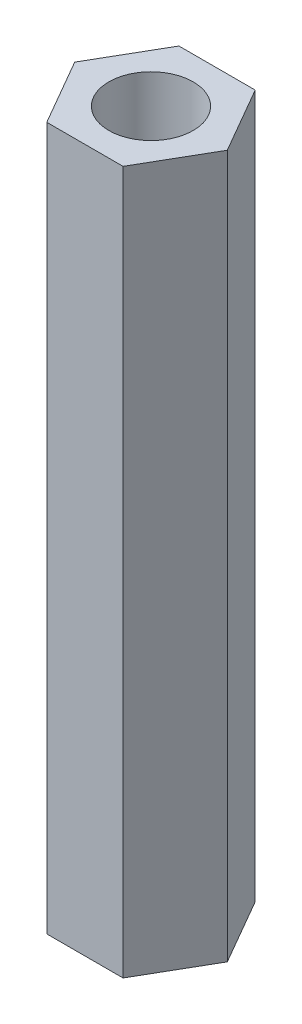
SolidWorks part; units mm, degrees
material "黄铜"
ref_plane "前视基准面" through (0, 0, 0) normal (0, 0, 1) x (1, 0, 0)
ref_plane "上视基准面" through (0, 0, 0) normal (0, 1, 0) x (1, 0, 0)
ref_plane "右视基准面" through (0, 0, 0) normal (1, 0, 0) x (0, 0, -1)
other "Configuration Table"
sketch "草图1" plane through (0, 0, 0) normal (0, 1, 0) x (1, 0, 0)
  line L0 (-2.7135, 0) -> (2.7135, 0) construction
  line L1 (1.3568, -2.35) -> (2.7135, 0)
  line L2 (2.7135, 0) -> (1.3568, 2.35)
  line L3 (1.3568, 2.35) -> (-1.3568, 2.35)
  line L4 (-1.3568, 2.35) -> (-2.7135, 0)
  line L5 (-2.7135, 0) -> (-1.3568, -2.35)
  line L6 (-1.3568, -2.35) -> (1.3568, -2.35)
  circle A0 centre (0, 0) radius 2.35 construction
  circle A1 centre (0, 0) radius 1.5
  point P13 (0, 0)
  dimension "D2" = 3
  dimension "D1" = 4.7
extrude "凸台-拉伸1" add sketch "草图1" along normal blind 25
